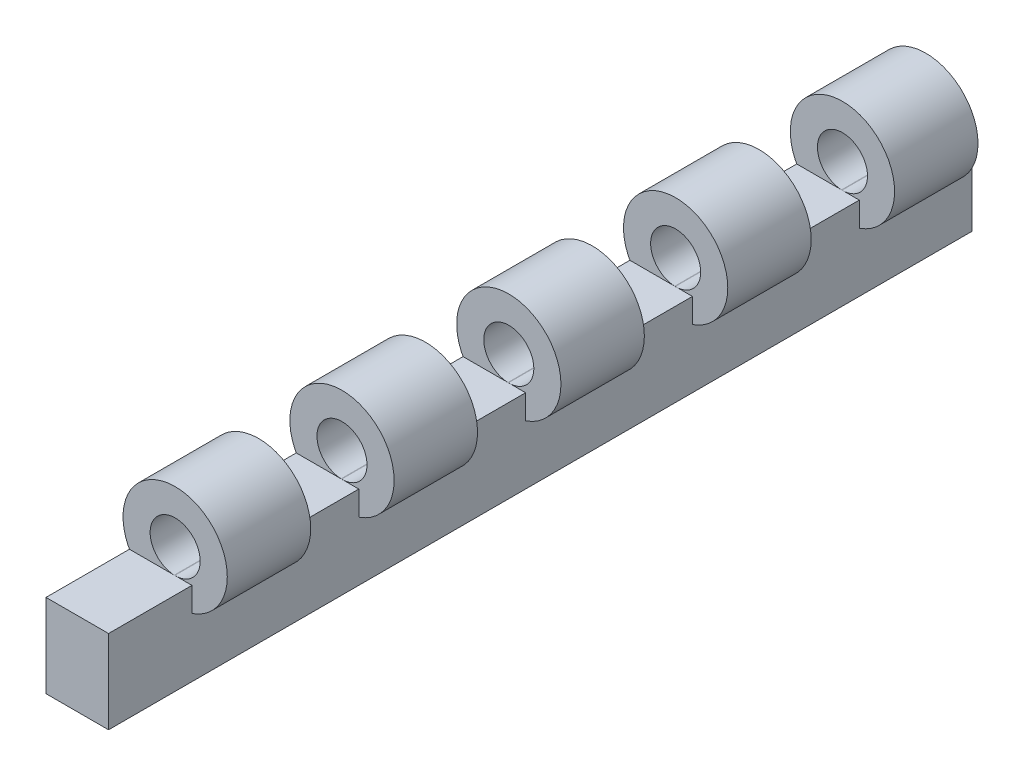
SolidWorks part; units mm, degrees
ref_plane "Front Plane" through (0, 0, 0) normal (0, 0, 1) x (1, 0, 0)
ref_plane "Top Plane" through (0, 0, 0) normal (0, 1, 0) x (1, 0, 0)
ref_plane "Right Plane" through (0, 0, 0) normal (1, 0, 0) x (0, 0, -1)
sketch "Sketch1" plane through (0, 0, 0) normal (0, 1, 0) x (1, 0, 0)
  line L0 (0, 103.5) -> (0, -103.5)
  line L1 (0, 103.5) -> (15, 103.5)
  line L2 (15, 103.5) -> (15, -103.5)
  line L3 (15, -103.5) -> (0, -103.5)
  point P4 (0, 0)
  point P8 (0, 103.5)
  dimension "D1" = 207
  dimension "D2" = 15
extrude "Boss-Extrude1" add sketch "Sketch1" along normal blind 20
ref_plane "Plane1" through (0, 0, 83.5) normal (0, 0, 1) x (1, 0, 0)
sketch "Sketch2" plane through (0, 0, 83.5) normal (0, 0, 1) x (1, 0, 0)
  circle A0 centre (10.969, 25.9942) radius 12.5
  circle A1 centre (10.969, 25.9942) radius 6
  dimension "D1" = 25
extrude "Boss-Extrude3" add sketch "Sketch2" against normal blind 20 separate body
pattern_linear "LPattern2" count 5 spacing 40 along (0, 0, -1) of "Boss-Extrude3"
